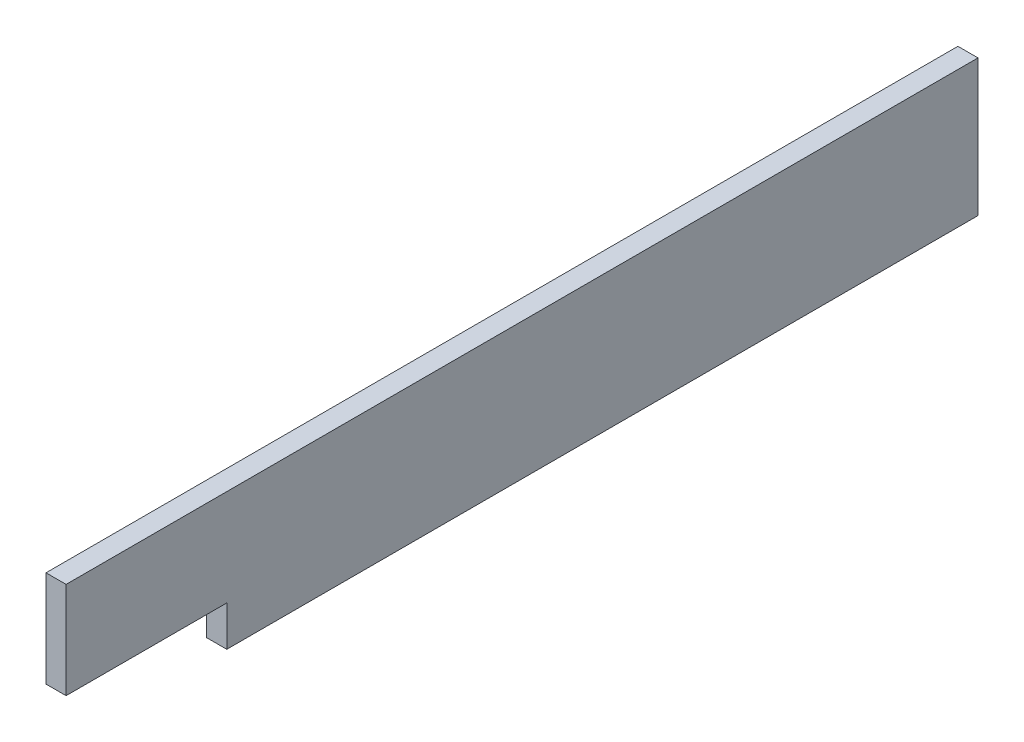
SolidWorks part; units mm, degrees
ref_plane "Front Plane" through (0, 0, 0) normal (0, 0, 1) x (1, 0, 0)
ref_plane "Top Plane" through (0, 0, 0) normal (0, 1, 0) x (1, 0, 0)
ref_plane "Right Plane" through (0, 0, 0) normal (1, 0, 0) x (0, 0, -1)
sketch "Sketch1" plane through (0, 0, 0) normal (0, 0, 1) x (1, 0, 0)
  line L1 (0, 0) -> (6.35, 0)
  line L2 (0, 0) -> (0, 43.18)
  line L3 (0, 43.18) -> (6.35, 43.18)
  line L4 (6.35, 0) -> (6.35, 43.18)
  dimension "D1" = 6.35
  dimension "D2" = 43.18
extrude "Boss-Extrude1" add sketch "Sketch1" along normal blind 288.29
sketch "Sketch2" plane through (0, 0, 0) normal (-1, 0, 0) x (0, 0, 1)
  line L1 (288.29, 0) -> (237.49, 0)
  line L2 (288.29, 0) -> (288.29, 12.7)
  line L3 (288.29, 12.7) -> (237.49, 12.7)
  line L4 (237.49, 0) -> (237.49, 12.7)
  dimension "D1" = 50.8
  dimension "D2" = 12.7
extrude "Cut-Extrude1" cut sketch "Sketch2" against normal up to next
